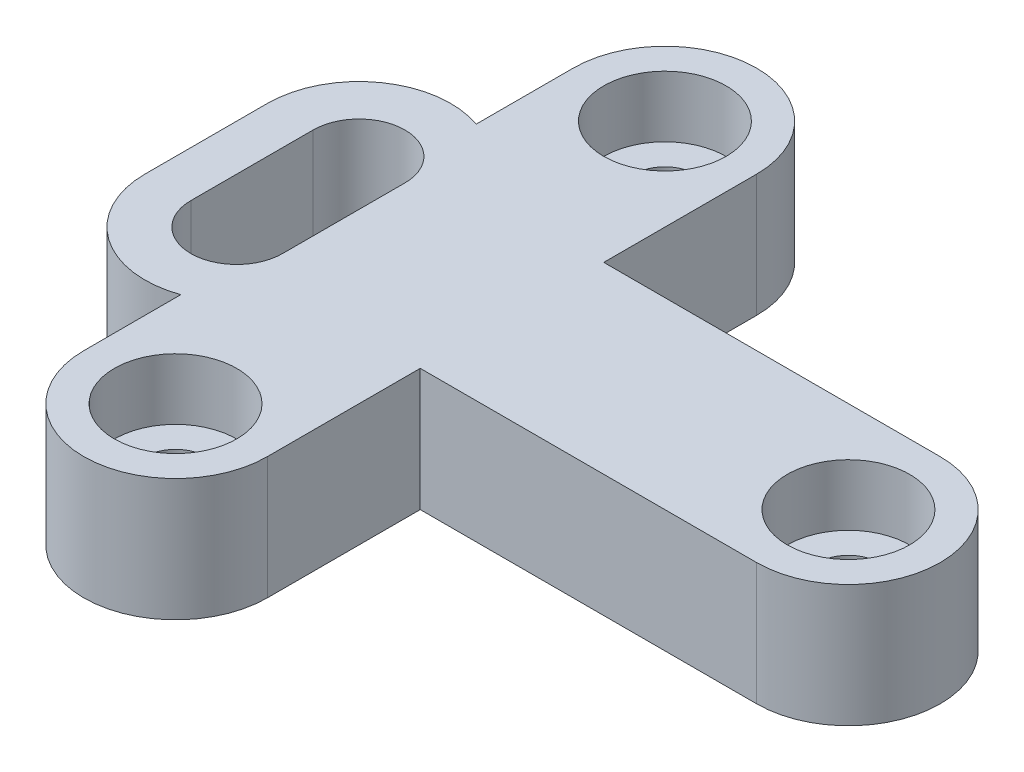
SolidWorks part; units mm, degrees
ref_plane "Front Plane" through (0, 0, 0) normal (0, 0, 1) x (1, 0, 0)
ref_plane "Top Plane" through (0, 0, 0) normal (0, 1, 0) x (1, 0, 0)
ref_plane "Right Plane" through (0, 0, 0) normal (1, 0, 0) x (0, 0, -1)
sketch "Sketch1" plane through (0, 0, 0) normal (0, 1, 0) x (1, 0, 0)
  line L0 (0, 10) -> (0, -10) construction
  line L1 (7.5, 10) -> (7.5, -10)
  line L2 (-7.5, 10) -> (-7.5, -10)
  line L3 (35, -40) -> (35, -15)
  line L4 (35, -15) -> (90, -15)
  line L5 (20, 40) -> (20, -49960) construction
  line L6 (90, 15) -> (35, 15)
  line L7 (35, 15) -> (35, 40)
  line L8 (5, 40) -> (5, 24.1421)
  line L9 (-15, 10) -> (-15, -10)
  line L10 (5, -40) -> (5, -24.1421)
  line L11 (20, 40) -> (50020, 40) construction
  line L12 (20, -40) -> (-49980, -40) construction
  circle A0 centre (20, -40) radius 5
  circle A1 centre (20, 40) radius 5
  circle A2 centre (90, 0) radius 5
  arc A3 (7.5, 10) -> (-7.5, 10) centre (0, 10) ccw
  arc A4 (-7.5, -10) -> (7.5, -10) centre (0, -10) ccw
  arc A5 (5, -40) -> (35, -40) centre (20, -40) ccw
  arc A6 (35, 40) -> (5, 40) centre (20, 40) ccw
  arc A7 (90, -15) -> (90, 15) centre (90, 0) ccw
  arc A8 (5, 24.1421) -> (-15, 10) centre (0, 10) ccw
  arc A10 (-15, -10) -> (5, -24.1421) centre (0, -10) ccw
  point P8 (0, 0)
  point P13 (0, 0)
  dimension "D1" = 80
  dimension "D2" = 40
  dimension "D3" = 30
  dimension "D4" = 20
  dimension "D12" = 10
  dimension "D13" = 10
  dimension "D14" = 15
  dimension "D15" = 15
  dimension "D8" = 15
  dimension "D9" = 15
  dimension "D10" = 15
  dimension "D11" = 10
  dimension "D6" = 7.5
  dimension "D5" = 70
  dimension "D7" = 20
extrude "Boss-Extrude1" add sketch "Sketch1" along normal mid plane 20
sketch "Sketch2" plane through (0, 10, 0) normal (0, 1, 0) x (1, 0, 0)
  circle A0 centre (20, -40) radius 10
  circle A1 centre (20, 40) radius 10
  circle A2 centre (90, 0) radius 10
  dimension "D1" = 20
  dimension "D2" = 20
  dimension "D3" = 20
extrude "Cut-Extrude1" cut sketch "Sketch2" against normal blind 10
